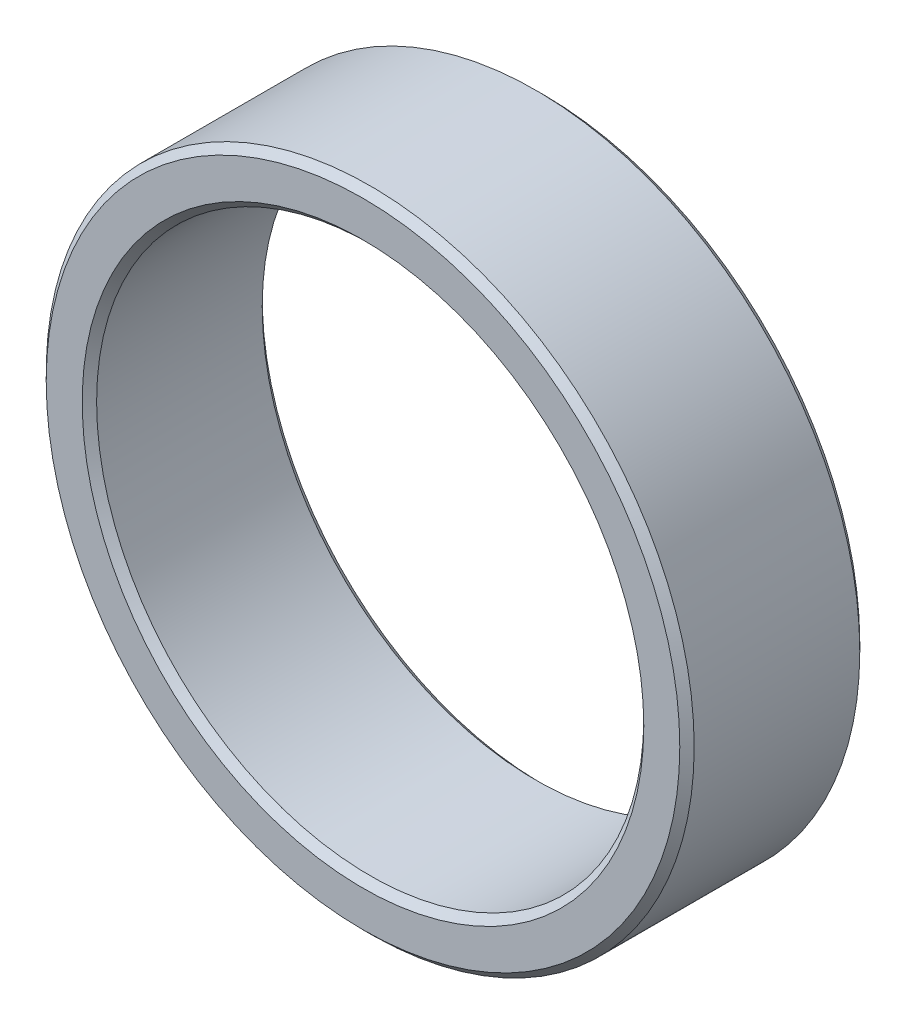
SolidWorks part; units mm, degrees
ref_plane "Front Plane" through (0, 0, 0) normal (0, 0, 1) x (1, 0, 0)
ref_plane "Top Plane" through (0, 0, 0) normal (0, 1, 0) x (1, 0, 0)
ref_plane "Right Plane" through (0, 0, 0) normal (1, 0, 0) x (0, 0, -1)
sketch "Sketch1" plane through (0, 0, 0) normal (0, 0, 1) x (1, 0, 0)
  circle A0 centre (0, 0) radius 9
  circle A1 centre (0, 0) radius 7.6
  dimension "D1" = 18
  dimension "D2" = 15.2
extrude "Boss-Extrude1" add sketch "Sketch1" along normal blind 5
chamfer "Chamfer1" distance 0.2 angle 45 4 edges at (7.6, 0, 0) (9, 0, 0) (9, 0, 5) (7.6, 0, 5)
